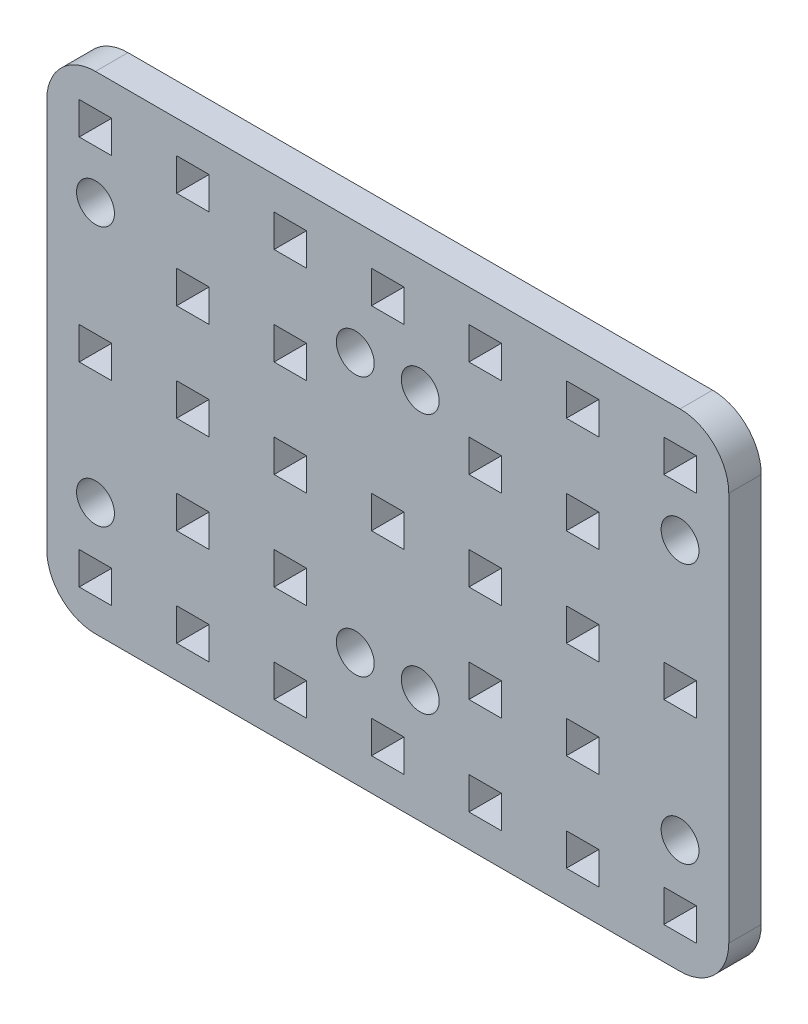
SolidWorks part; units mm, degrees
ref_plane "Alzado" through (0, 0, 0) normal (0, 0, 1) x (1, 0, 0)
ref_plane "Planta" through (0, 0, 0) normal (0, 1, 0) x (1, 0, 0)
ref_plane "Vista lateral" through (0, 0, 0) normal (1, 0, 0) x (0, 0, -1)
sketch "Model" plane through (0, 0, 0) normal (0, 0, 1) x (1, 0, 0)
  line L0 (9.4229, 291.9634) -> (9.4229, 288.9634)
  line L1 (12.4229, 291.9634) -> (9.4229, 291.9634)
  line L2 (12.4229, 288.9634) -> (12.4229, 291.9634)
  line L3 (9.4229, 288.9634) -> (12.4229, 288.9634)
  line L4 (18.4229, 291.9634) -> (18.4229, 288.9634)
  line L5 (21.4229, 291.9634) -> (18.4229, 291.9634)
  line L6 (21.4229, 288.9634) -> (21.4229, 291.9634)
  line L7 (18.4229, 288.9634) -> (21.4229, 288.9634)
  line L8 (27.4229, 291.9634) -> (27.4229, 288.9634)
  line L9 (30.4229, 291.9634) -> (27.4229, 291.9634)
  line L10 (30.4229, 288.9634) -> (30.4229, 291.9634)
  line L11 (27.4229, 288.9634) -> (30.4229, 288.9634)
  line L12 (54.4229, 291.9634) -> (54.4229, 288.9634)
  line L13 (57.4229, 291.9634) -> (54.4229, 291.9634)
  line L14 (57.4229, 288.9634) -> (57.4229, 291.9634)
  line L15 (54.4229, 288.9634) -> (57.4229, 288.9634)
  line L16 (63.4229, 291.9634) -> (63.4229, 288.9634)
  line L17 (66.4229, 291.9634) -> (63.4229, 291.9634)
  line L18 (66.4229, 288.9634) -> (66.4229, 291.9634)
  line L19 (63.4229, 288.9634) -> (66.4229, 288.9634)
  line L20 (9.4229, 255.9634) -> (9.4229, 252.9634)
  line L21 (12.4229, 255.9634) -> (9.4229, 255.9634)
  line L22 (12.4229, 252.9634) -> (12.4229, 255.9634)
  line L23 (9.4229, 252.9634) -> (12.4229, 252.9634)
  line L24 (18.4229, 255.9634) -> (18.4229, 252.9634)
  line L25 (21.4229, 255.9634) -> (18.4229, 255.9634)
  line L26 (21.4229, 252.9634) -> (21.4229, 255.9634)
  line L27 (18.4229, 252.9634) -> (21.4229, 252.9634)
  line L28 (27.4229, 255.9634) -> (27.4229, 252.9634)
  line L29 (30.4229, 255.9634) -> (27.4229, 255.9634)
  line L30 (30.4229, 252.9634) -> (30.4229, 255.9634)
  line L31 (27.4229, 252.9634) -> (30.4229, 252.9634)
  line L32 (54.4229, 255.9634) -> (54.4229, 252.9634)
  line L33 (57.4229, 255.9634) -> (54.4229, 255.9634)
  line L34 (57.4229, 252.9634) -> (57.4229, 255.9634)
  line L35 (54.4229, 252.9634) -> (57.4229, 252.9634)
  line L36 (63.4229, 255.9634) -> (63.4229, 252.9634)
  line L37 (66.4229, 255.9634) -> (63.4229, 255.9634)
  line L38 (66.4229, 252.9634) -> (66.4229, 255.9634)
  line L39 (63.4229, 252.9634) -> (66.4229, 252.9634)
  line L40 (18.4229, 264.9634) -> (18.4229, 261.9634)
  line L41 (21.4229, 264.9634) -> (18.4229, 264.9634)
  line L42 (21.4229, 261.9634) -> (21.4229, 264.9634)
  line L43 (18.4229, 261.9634) -> (21.4229, 261.9634)
  line L44 (27.4229, 264.9634) -> (27.4229, 261.9634)
  line L45 (30.4229, 264.9634) -> (27.4229, 264.9634)
  line L46 (30.4229, 261.9634) -> (30.4229, 264.9634)
  line L47 (27.4229, 261.9634) -> (30.4229, 261.9634)
  line L48 (54.4229, 264.9634) -> (54.4229, 261.9634)
  line L49 (57.4229, 264.9634) -> (54.4229, 264.9634)
  line L50 (57.4229, 261.9634) -> (57.4229, 264.9634)
  line L51 (54.4229, 261.9634) -> (57.4229, 261.9634)
  line L52 (36.4229, 291.9634) -> (36.4229, 288.9634)
  line L53 (39.4229, 291.9634) -> (36.4229, 291.9634)
  line L54 (39.4229, 288.9634) -> (39.4229, 291.9634)
  line L55 (36.4229, 288.9634) -> (39.4229, 288.9634)
  line L56 (45.4229, 291.9634) -> (45.4229, 288.9634)
  line L57 (48.4229, 291.9634) -> (45.4229, 291.9634)
  line L58 (48.4229, 288.9634) -> (48.4229, 291.9634)
  line L59 (45.4229, 288.9634) -> (48.4229, 288.9634)
  line L60 (36.4229, 255.9634) -> (36.4229, 252.9634)
  line L61 (39.4229, 255.9634) -> (36.4229, 255.9634)
  line L62 (39.4229, 252.9634) -> (39.4229, 255.9634)
  line L63 (36.4229, 252.9634) -> (39.4229, 252.9634)
  line L64 (45.4229, 255.9634) -> (45.4229, 252.9634)
  line L65 (48.4229, 255.9634) -> (45.4229, 255.9634)
  line L66 (48.4229, 252.9634) -> (48.4229, 255.9634)
  line L67 (45.4229, 252.9634) -> (48.4229, 252.9634)
  line L68 (45.4229, 264.9634) -> (45.4229, 261.9634)
  line L69 (48.4229, 264.9634) -> (45.4229, 264.9634)
  line L70 (48.4229, 261.9634) -> (48.4229, 264.9634)
  line L71 (45.4229, 261.9634) -> (48.4229, 261.9634)
  line L72 (9.4229, 273.9634) -> (9.4229, 270.9634)
  line L73 (12.4229, 273.9634) -> (9.4229, 273.9634)
  line L74 (12.4229, 270.9634) -> (12.4229, 273.9634)
  line L75 (9.4229, 270.9634) -> (12.4229, 270.9634)
  line L76 (18.4229, 273.9634) -> (18.4229, 270.9634)
  line L77 (21.4229, 273.9634) -> (18.4229, 273.9634)
  line L78 (21.4229, 270.9634) -> (21.4229, 273.9634)
  line L79 (18.4229, 270.9634) -> (21.4229, 270.9634)
  line L80 (27.4229, 273.9634) -> (27.4229, 270.9634)
  line L81 (30.4229, 273.9634) -> (27.4229, 273.9634)
  line L82 (30.4229, 270.9634) -> (30.4229, 273.9634)
  line L83 (27.4229, 270.9634) -> (30.4229, 270.9634)
  line L84 (54.4229, 273.9634) -> (54.4229, 270.9634)
  line L85 (57.4229, 273.9634) -> (54.4229, 273.9634)
  line L86 (57.4229, 270.9634) -> (57.4229, 273.9634)
  line L87 (54.4229, 270.9634) -> (57.4229, 270.9634)
  line L88 (63.4229, 273.9634) -> (63.4229, 270.9634)
  line L89 (66.4229, 273.9634) -> (63.4229, 273.9634)
  line L90 (66.4229, 270.9634) -> (66.4229, 273.9634)
  line L91 (63.4229, 270.9634) -> (66.4229, 270.9634)
  line L92 (18.4229, 282.9634) -> (18.4229, 279.9634)
  line L93 (21.4229, 282.9634) -> (18.4229, 282.9634)
  line L94 (21.4229, 279.9634) -> (21.4229, 282.9634)
  line L95 (18.4229, 279.9634) -> (21.4229, 279.9634)
  line L96 (27.4229, 282.9634) -> (27.4229, 279.9634)
  line L97 (30.4229, 282.9634) -> (27.4229, 282.9634)
  line L98 (30.4229, 279.9634) -> (30.4229, 282.9634)
  line L99 (27.4229, 279.9634) -> (30.4229, 279.9634)
  line L100 (54.4229, 282.9634) -> (54.4229, 279.9634)
  line L101 (57.4229, 282.9634) -> (54.4229, 282.9634)
  line L102 (57.4229, 279.9634) -> (57.4229, 282.9634)
  line L103 (54.4229, 279.9634) -> (57.4229, 279.9634)
  line L104 (36.4229, 273.9634) -> (36.4229, 270.9634)
  line L105 (39.4229, 273.9634) -> (36.4229, 273.9634)
  line L106 (39.4229, 270.9634) -> (39.4229, 273.9634)
  line L107 (36.4229, 270.9634) -> (39.4229, 270.9634)
  line L108 (45.4229, 273.9634) -> (45.4229, 270.9634)
  line L109 (48.4229, 273.9634) -> (45.4229, 273.9634)
  line L110 (48.4229, 270.9634) -> (48.4229, 273.9634)
  line L111 (45.4229, 270.9634) -> (48.4229, 270.9634)
  line L112 (45.4229, 282.9634) -> (45.4229, 279.9634)
  line L113 (48.4229, 282.9634) -> (45.4229, 282.9634)
  line L114 (48.4229, 279.9634) -> (48.4229, 282.9634)
  line L115 (45.4229, 279.9634) -> (48.4229, 279.9634)
  line L116 (10.9229, 294.9634) -> (64.9229, 294.9634)
  line L117 (10.9229, 249.9634) -> (64.9229, 249.9634)
  line L118 (6.4229, 290.4634) -> (6.4229, 254.4634)
  line L119 (69.4229, 290.4634) -> (69.4229, 254.4634)
  arc A0 (69.4229, 290.4634) -> (64.9229, 294.9634) centre (64.9229, 290.4634) ccw
  arc A1 (64.9229, 249.9634) -> (69.4229, 254.4634) centre (64.9229, 254.4634) ccw
  arc A2 (10.9229, 294.9634) -> (6.4229, 290.4634) centre (10.9229, 290.4634) ccw
  arc A3 (6.4229, 254.4634) -> (10.9229, 249.9634) centre (10.9229, 254.4634) ccw
  circle A4 centre (64.9229, 284.4634) radius 1.75
  circle A5 centre (34.9229, 284.4634) radius 1.75
  circle A6 centre (64.9229, 260.4634) radius 1.75
  circle A7 centre (34.9229, 260.4634) radius 1.75
  circle A8 centre (40.9229, 284.4634) radius 1.75
  circle A9 centre (10.9229, 284.4634) radius 1.75
  circle A10 centre (40.9229, 260.4634) radius 1.75
  circle A11 centre (10.9229, 260.4634) radius 1.75
extrude "Saliente-Extruir1" add sketch "Model" along normal blind 3
